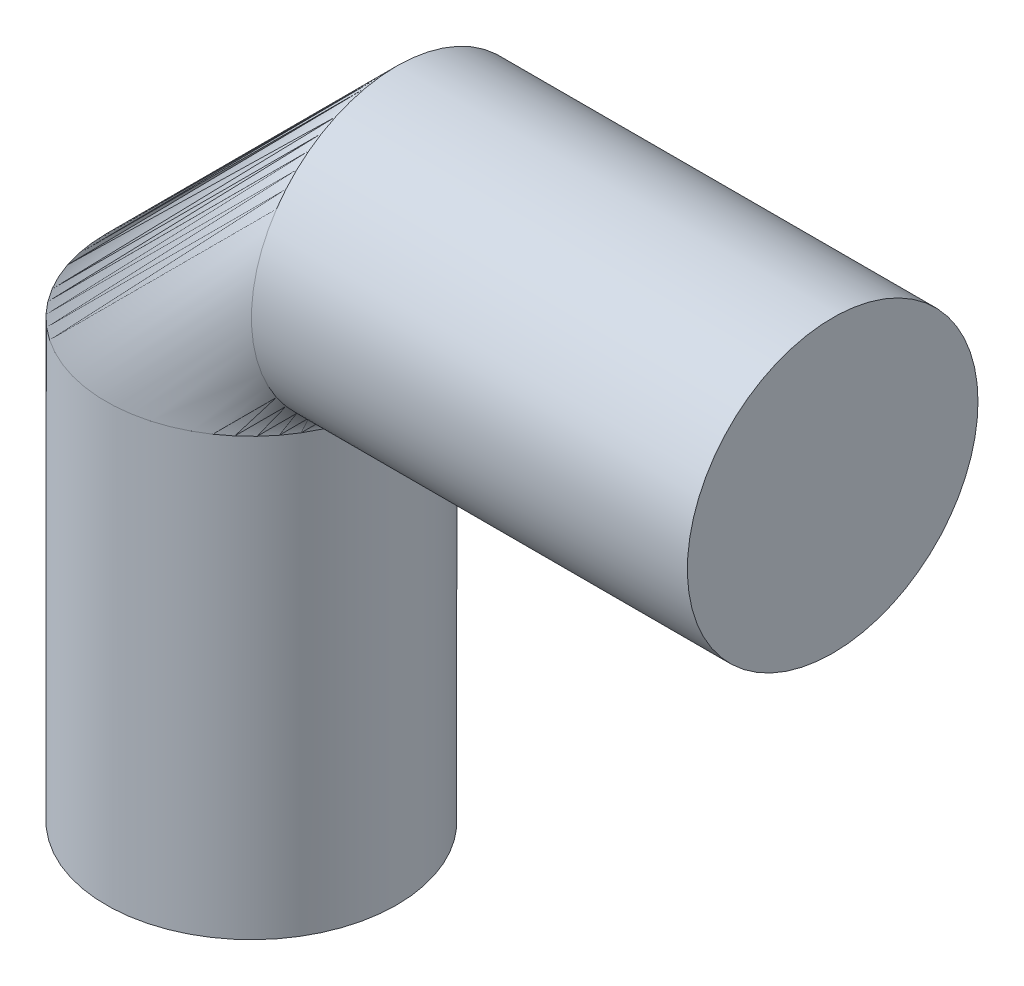
SolidWorks part; units mm, degrees
ref_plane "Front Plane" through (0, 0, 0) normal (0, 0, 1) x (1, 0, 0)
ref_plane "Top Plane" through (0, 0, 0) normal (0, 1, 0) x (1, 0, 0)
ref_plane "Right Plane" through (0, 0, 0) normal (1, 0, 0) x (0, 0, -1)
sketch "Sketch1" plane through (0, 0, 0) normal (0, 0, 1) x (1, 0, 0)
  line L0 (12.7, 0) -> (3.175, 0)
  line L1 (0, -3.175) -> (0, -12.7)
  arc A0 (3.175, 0) -> (0, -3.175) centre (3.175, -3.175) ccw
  point P6 (0, 0)
  dimension "D3" = 3.175
  dimension "D1" = 12.7
  dimension "D2" = 12.7
ref_plane "Plane1" through (12.7, 0, 0) normal (1, 0, 0) x (0, 0, -1)
sketch "Sketch2" plane through (12.7, 0, 0) normal (1, 0, 0) x (0, 0, -1)
  circle A0 centre (0, 0) radius 3.175
  dimension "D1" = 6.35
sweep "Sweep1" add profiles "Sketch2" path "Sketch1"
